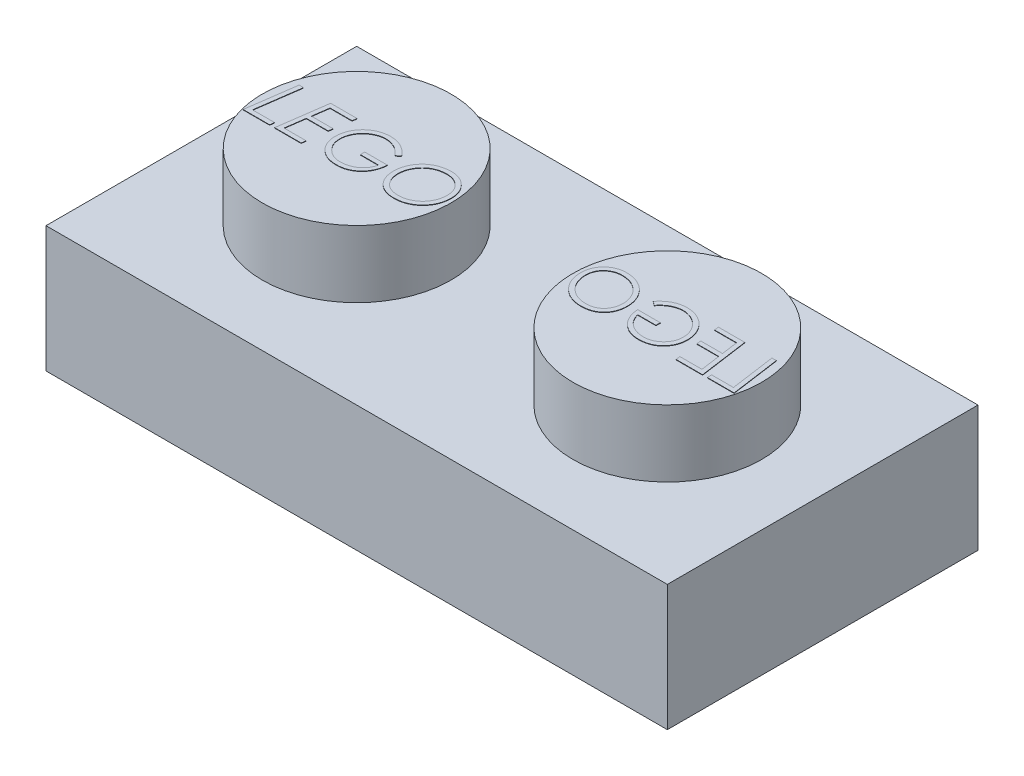
SolidWorks part; units mm, degrees
ref_plane "Front Plane" through (0, 0, 0) normal (0, 0, 1) x (1, 0, 0)
ref_plane "Top Plane" through (0, 0, 0) normal (0, 1, 0) x (1, 0, 0)
ref_plane "Right Plane" through (0, 0, 0) normal (1, 0, 0) x (0, 0, -1)
sketch "Sketch1" plane through (0, 0, 0) normal (0, 1, 0) x (1, 0, 0)
  line L0 (0, 0) -> (7.9, 0)
  line L1 (7.9, 0) -> (7.9, 7.9)
  line L2 (0, 0) -> (0, 7.9)
  line L3 (0, 7.9) -> (7.9, 7.9)
  dimension "D1" = 7.9
  dimension "D2" = 7.9
  dimension "D3" = 7.9
extrude "Boss-Extrude1" add sketch "Sketch1" along normal blind 3.2
sketch "Sketch2" plane through (0, 3.2, 0) normal (0, 1, 0) x (1, 0, 0)
  line L0 (0, 7.9) -> (7.9, 0) construction
  circle A0 centre (3.95, 3.95) radius 2.4
extrude "Boss-Extrude2" add sketch "Sketch2" along normal blind 1.7
sketch "Sketch3" plane through (0, 4.9, 0) normal (0, 1, 0) x (1, 0, 0)
  line L0 (1.625, 3.3549) -> (6.275, 3.3549) construction
  circle A0 centre (3.95, 3.95) radius 2.4 construction
  circle A1 centre (3.95, 3.95) radius 2.4 construction
  text T0 "<i>LEGO</i>" font "Century Gothic" height 1.25
extrude "Boss-Extrude4" add sketch "Sketch3" along normal blind 0.01
sketch "Sketch4" plane through (0, 0, 0) normal (0, -1, 0) x (1, 0, 0)
  line L0 (7.9, -7.9) -> (0, -7.9) construction
  line L1 (7.3, -7.3) -> (0.6204, -7.3)
  line L2 (7.3, -7.3) -> (7.3, -0.6204)
  line L3 (7.3, -0.6204) -> (0.6204, -0.6204)
  line L4 (0.6204, -7.3) -> (0.6204, -0.6204)
  line L5 (7.9, 0) -> (7.9, -7.9) construction
  dimension "D1" = 0.6
  dimension "D2" = 0.6
extrude "Cut-Extrude1" cut sketch "Sketch4" against normal blind 2.01 contours L2 L1 L4 L3
sketch "Sketch5" plane through (0, 3.2, 0) normal (0, 1, 0) x (1, 0, 0)
  line L1 (1.4581, 1.5578) -> (6.3695, 1.5578)
  line L2 (1.4581, 1.5578) -> (1.4581, 6.3652)
  line L3 (1.4581, 6.3652) -> (6.3695, 6.3652)
  line L4 (6.3695, 1.5578) -> (6.3695, 6.3652)
  circle A1 centre (6.3695, 6.3652) radius 1.0161
  circle A2 centre (6.3695, 1.5578) radius 1.0061
  circle A3 centre (1.4581, 1.5578) radius 1.0219
  circle A4 centre (1.4581, 6.3652) radius 1.0411
  circle M5 centre (3.95, 3.95) radius 2.4
extrude "Boss-Extrude5" add sketch "Sketch5" against normal blind 2.01 contours L1 A2 L4 | L2 A3 L1 | L1 A3 L2 | L4 A2 L1 M5 | L4 A1 L3 | L3 A1 L4 | L2 A4 L3 | L3 A4 L2
mirror "Mirror1" about plane through (7.9, 3.2, 0) normal (-1, 0, 0) of bodies 106
